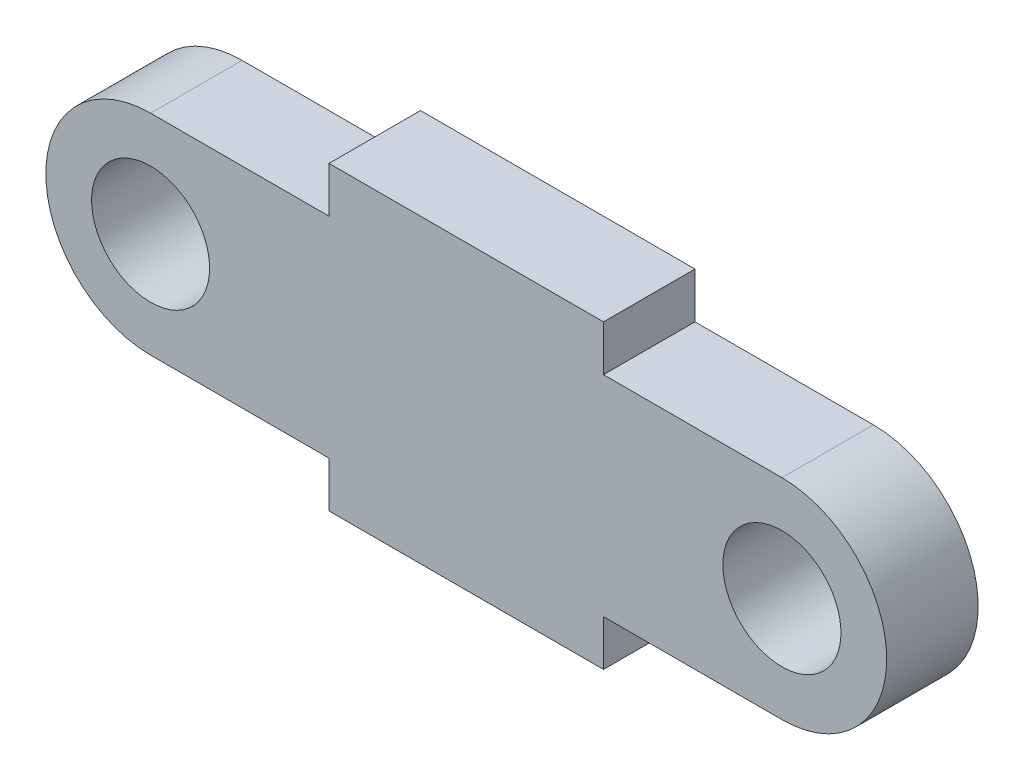
SolidWorks part; units mm, degrees
ref_plane "Front Plane" through (0, 0, 0) normal (0, 0, 1) x (1, 0, 0)
ref_plane "Top Plane" through (0, 0, 0) normal (0, 1, 0) x (1, 0, 0)
ref_plane "Right Plane" through (0, 0, 0) normal (1, 0, 0) x (0, 0, -1)
sketch "Sketch1" plane through (0, 0, 0) normal (0, 0, 1) x (1, 0, 0)
  line L0 (-5.1175, 68.0301) -> (-5.1175, -84.9828) construction
  line L1 (-39.6175, 11.45) -> (-20.1175, 11.45)
  line L2 (-20.1175, 11.45) -> (-20.1175, 16.45)
  line L3 (-20.1175, 16.45) -> (9.8825, 16.45)
  line L4 (-39.6175, -11.45) -> (-20.1175, -11.45)
  line L5 (-20.1175, -11.45) -> (-20.1175, -16.45)
  line L6 (-20.1175, -16.45) -> (9.8825, -16.45)
  line L7 (9.8825, -11.45) -> (9.8825, -16.45)
  line L8 (29.3825, -11.45) -> (9.8825, -11.45)
  line L9 (9.8825, 11.45) -> (9.8825, 16.45)
  line L10 (29.3825, 11.45) -> (9.8825, 11.45)
  circle A0 centre (-39.6175, 0) radius 6.45
  arc A1 (-39.6175, 11.45) -> (-39.6175, -11.45) centre (-39.6175, 0) ccw
  arc A2 (29.3825, 11.45) -> (29.3825, -11.45) centre (29.3825, 0) cw
  circle A3 centre (29.3825, 0) radius 6.45
  point P26 (-5.1175, -16.45)
  point P28 (-5.1175, 16.45)
  dimension "D1" = 12.9
  dimension "D3" = 22.9
  dimension "D7" = 22.9
  dimension "D2" = 34.5
  dimension "D4" = 5
  dimension "D5" = 5
  dimension "D6" = 15
extrude "Boss-Extrude1" add sketch "Sketch1" against normal blind 10
